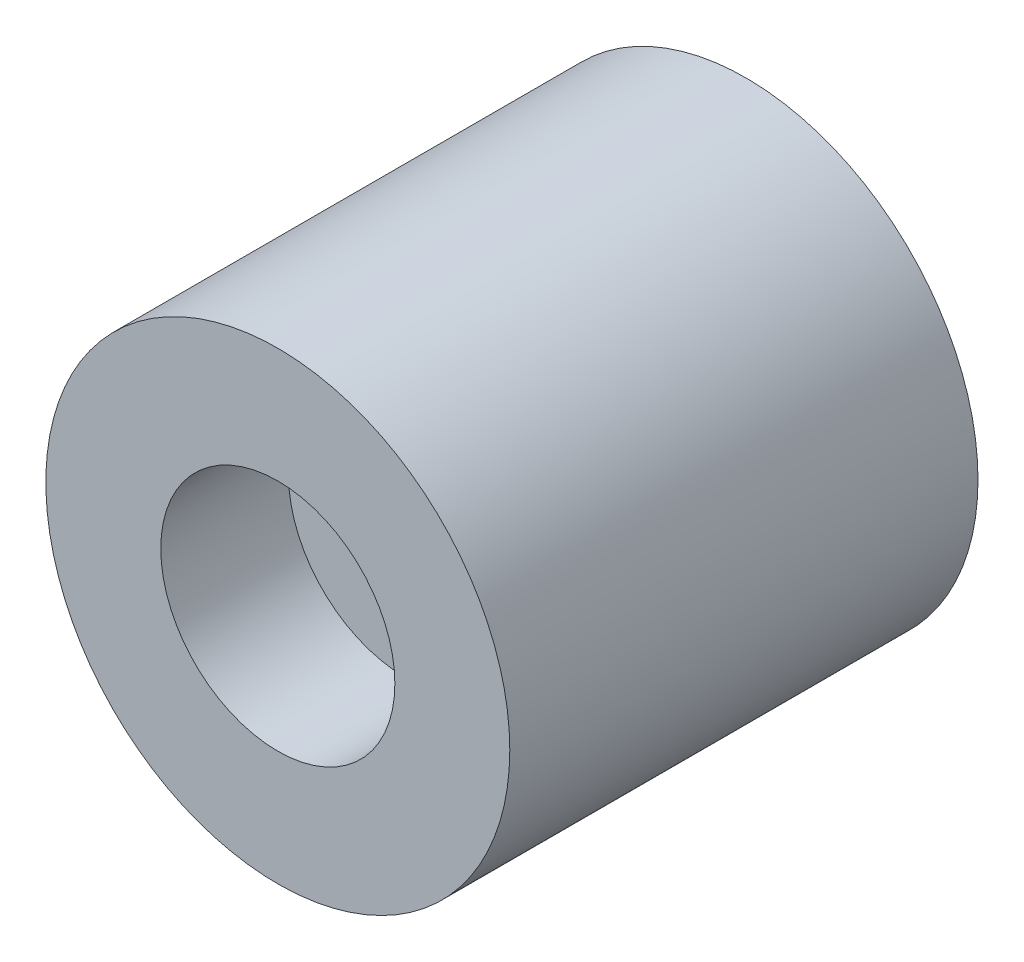
SolidWorks part; units mm, degrees
ref_plane "Front Plane" through (0, 0, 0) normal (0, 0, 1) x (1, 0, 0)
ref_plane "Top Plane" through (0, 0, 0) normal (0, 1, 0) x (1, 0, 0)
ref_plane "Right Plane" through (0, 0, 0) normal (1, 0, 0) x (0, 0, -1)
sketch "Sketch1" plane through (0, 0, 0) normal (0, 0, 1) x (1, 0, 0)
  circle A0 centre (0, 0) radius 5.45
  dimension "D1" = 10.9
extrude "Boss-Extrude1" add sketch "Sketch1" along normal blind 11 contours A0
sketch "Sketch2" plane through (0, 0, 11) normal (0, 0, 1) x (1, 0, 0)
  circle A0 centre (0, 0) radius 2.75
  dimension "D1" = 5.5
extrude "Cut-Extrude1" cut sketch "Sketch2" against normal blind 3
sketch "Sketch3" plane through (0, 0, 11) normal (0, 0, 1) x (1, 0, 0)
  circle A0 centre (0, 0) radius 5.45
  dimension "D1" = 10.9
